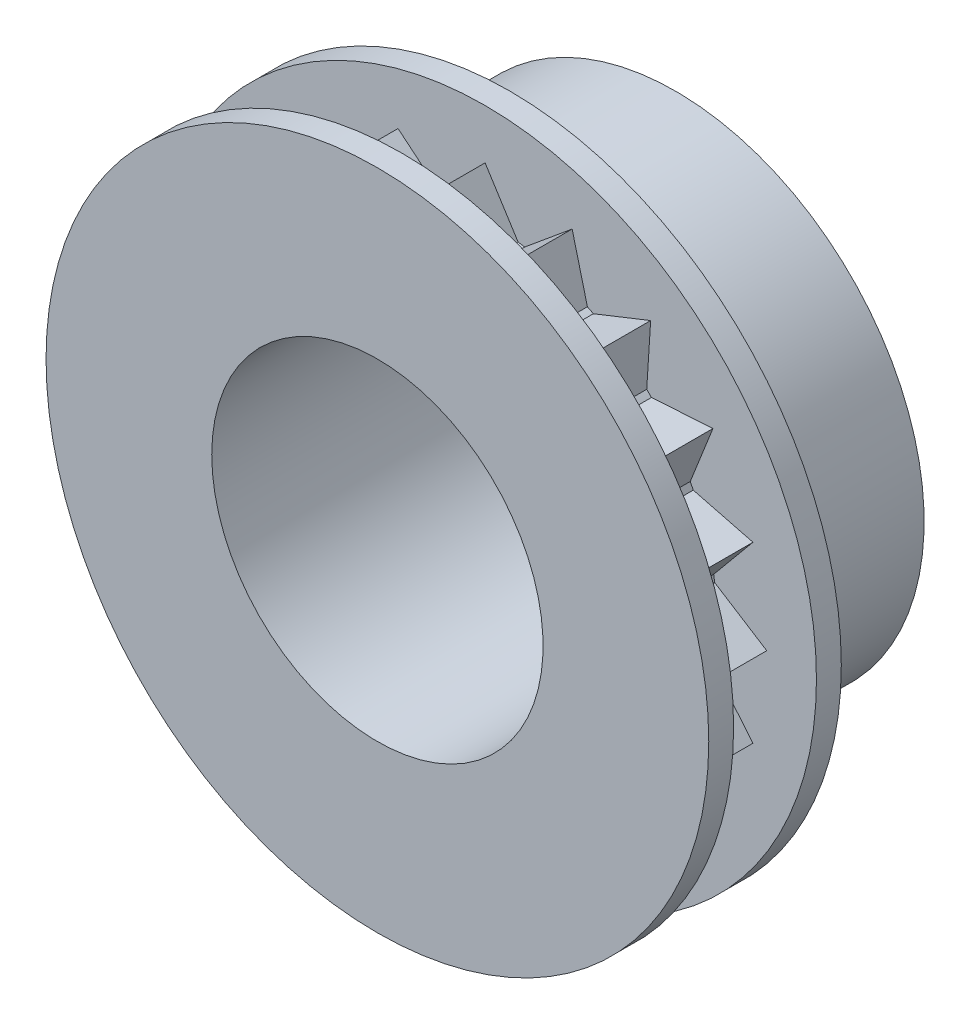
SolidWorks part; units mm, degrees
ref_plane "Front Plane" through (0, 0, 0) normal (0, 0, 1) x (1, 0, 0)
ref_plane "Top Plane" through (0, 0, 0) normal (0, 1, 0) x (1, 0, 0)
ref_plane "Right Plane" through (0, 0, 0) normal (1, 0, 0) x (0, 0, -1)
sketch "Sketch1" plane through (0, 0, 0) normal (0, 0, 1) x (1, 0, 0)
  line L0 (0, 31.211) -> (0, 12) construction
  line L1 (0, 17) -> (-1.9906, 13.8578)
  line L2 (0, 17) -> (1.9906, 13.8578)
  line L3 (5.2533, 16.168) -> (2.3891, 13.7946)
  line L4 (5.2533, 16.168) -> (6.1755, 12.5644)
  line L5 (9.9923, 13.7533) -> (6.5349, 12.3812)
  line L6 (9.9923, 13.7533) -> (9.7558, 10.0411)
  line L7 (13.7533, 9.9923) -> (10.0411, 9.7558)
  line L8 (13.7533, 9.9923) -> (12.3812, 6.5349)
  line L9 (16.168, 5.2533) -> (12.5644, 6.1755)
  line L10 (16.168, 5.2533) -> (13.7946, 2.3891)
  line L11 (17, 0) -> (13.8578, 1.9906)
  line L12 (17, 0) -> (13.8578, -1.9906)
  line L13 (16.168, -5.2533) -> (13.7946, -2.3891)
  line L14 (16.168, -5.2533) -> (12.5644, -6.1755)
  line L15 (13.7533, -9.9923) -> (12.3812, -6.5349)
  line L16 (13.7533, -9.9923) -> (10.0411, -9.7558)
  line L17 (9.9923, -13.7533) -> (9.7558, -10.0411)
  line L18 (9.9923, -13.7533) -> (6.5349, -12.3812)
  line L19 (5.2533, -16.168) -> (6.1755, -12.5644)
  line L20 (5.2533, -16.168) -> (2.3891, -13.7946)
  line L21 (0, -17) -> (1.9906, -13.8578)
  line L22 (0, -17) -> (-1.9906, -13.8578)
  line L23 (-5.2533, -16.168) -> (-2.3891, -13.7946)
  line L24 (-5.2533, -16.168) -> (-6.1755, -12.5644)
  line L25 (-9.9923, -13.7533) -> (-6.5349, -12.3812)
  line L26 (-9.9923, -13.7533) -> (-9.7558, -10.0411)
  line L27 (-13.7533, -9.9923) -> (-10.0411, -9.7558)
  line L28 (-13.7533, -9.9923) -> (-12.3812, -6.5349)
  line L29 (-16.168, -5.2533) -> (-12.5644, -6.1755)
  line L30 (-16.168, -5.2533) -> (-13.7946, -2.3891)
  line L31 (-17, 0) -> (-13.8578, -1.9906)
  line L32 (-17, 0) -> (-13.8578, 1.9906)
  line L33 (-16.168, 5.2533) -> (-13.7946, 2.3891)
  line L34 (-16.168, 5.2533) -> (-12.5644, 6.1755)
  line L35 (-13.7533, 9.9923) -> (-12.3812, 6.5349)
  line L36 (-13.7533, 9.9923) -> (-10.0411, 9.7558)
  line L37 (-9.9923, 13.7533) -> (-9.7558, 10.0411)
  line L38 (-9.9923, 13.7533) -> (-6.5349, 12.3812)
  line L39 (-5.2533, 16.168) -> (-6.1755, 12.5644)
  line L40 (-5.2533, 16.168) -> (-2.3891, 13.7946)
  line L41 (0, -17) -> (0, -21.8805) construction
  arc A0 (-13.7946, 2.3891) -> (-13.8578, 1.9906) centre (0, 0) ccw
  circle A1 centre (0, 0) radius 17
  arc A2 (-13.8578, -1.9906) -> (-13.7946, -2.3891) centre (0, 0) ccw
  arc A3 (-12.5644, -6.1755) -> (-12.3812, -6.5349) centre (0, 0) ccw
  arc A4 (-10.0411, -9.7558) -> (-9.7558, -10.0411) centre (0, 0) ccw
  arc A5 (-12.3812, 6.5349) -> (-12.5644, 6.1755) centre (0, 0) ccw
  arc A6 (-9.7558, 10.0411) -> (-10.0411, 9.7558) centre (0, 0) ccw
  arc A7 (-6.1755, 12.5644) -> (-6.5349, 12.3812) centre (0, 0) ccw
  arc A8 (-1.9906, 13.8578) -> (-2.3891, 13.7946) centre (0, 0) ccw
  arc A9 (2.3891, 13.7946) -> (1.9906, 13.8578) centre (0, 0) ccw
  arc A10 (6.5349, 12.3812) -> (6.1755, 12.5644) centre (0, 0) ccw
  arc A11 (10.0411, 9.7558) -> (9.7558, 10.0411) centre (0, 0) ccw
  arc A12 (13.7946, -2.3891) -> (13.8578, -1.9906) centre (0, 0) ccw
  arc A13 (12.3812, -6.5349) -> (12.5644, -6.1755) centre (0, 0) ccw
  arc A14 (1.9906, -13.8578) -> (2.3891, -13.7946) centre (0, 0) ccw
  arc A15 (-2.3891, -13.7946) -> (-1.9906, -13.8578) centre (0, 0) ccw
  arc A16 (-6.5349, -12.3812) -> (-6.1755, -12.5644) centre (0, 0) ccw
  arc A17 (9.7558, -10.0411) -> (10.0411, -9.7558) centre (0, 0) ccw
  arc A18 (6.1755, -12.5644) -> (6.5349, -12.3812) centre (0, 0) ccw
  arc A19 (12.5644, 6.1755) -> (12.3812, 6.5349) centre (0, 0) ccw
  arc A20 (13.8578, 1.9906) -> (13.7946, 2.3891) centre (0, 0) ccw
  point P68 (0, 0)
  dimension "D1" = 28
  dimension "D2" = 34
  dimension "D3" = 20
extrude "Boss-Extrude1" add sketch "Sketch1" along normal blind 5 contours L11 A20 L10 L9 A19 L8 L7 A11 L6 L5 A10 L4 L3 A9 L2 L1 A8 L40 L39 A7 L38 L37 A6 L36 L35 A5 L34 L33 A0 L32 L31 A2 L30 L29 A3 L28 L27 A4 L26 L25 A16 L24 L23 A15 L22 L21 A14 L20 L19 A18 L18
sketch "Sketch2" plane through (0, 0, 0) normal (0, 0, -1) x (-1, 0, 0)
  circle A0 centre (0, 0) radius 20
  dimension "D1" = 40
extrude "Boss-Extrude2" add sketch "Sketch2" along normal blind 1.5
sketch "Sketch3" plane through (0, 0, 5) normal (0, 0, 1) x (1, 0, 0)
  circle A0 centre (0, 0) radius 20
  dimension "D1" = 40
extrude "Boss-Extrude3" add sketch "Sketch3" along normal blind 1.5
sketch "Sketch4" plane through (0, 0, 6.5) normal (0, 0, 1) x (1, 0, 0)
  circle A0 centre (0, 0) radius 13
  dimension "D1" = 26
extrude "Cut-Extrude1" cut sketch "Sketch4" against normal blind 11.5
sketch "Sketch5" plane through (0, 0, -1.5) normal (0, 0, -1) x (-1, 0, 0)
  circle A0 centre (0, 0) radius 13
  circle A1 centre (0, 0) radius 15
  dimension "D1" = 30
  dimension "D2" = 26
extrude "Boss-Extrude4" add sketch "Sketch5" along normal blind 10 contours A1
sketch "Sketch6" plane through (0, 0, -11.5) normal (0, 0, -1) x (-1, 0, 0)
  circle A0 centre (0, 0) radius 13
  dimension "D1" = 26
extrude "Cut-Extrude2" cut sketch "Sketch6" against normal blind 30
sketch "Sketch7" plane through (0, 0, -11.5) normal (0, 0, -1) x (-1, 0, 0)
  circle A0 centre (0, 0) radius 13
  circle A1 centre (0, 0) radius 10
  dimension "D1" = 20
extrude "Boss-Extrude5" add sketch "Sketch7" against normal blind 18
